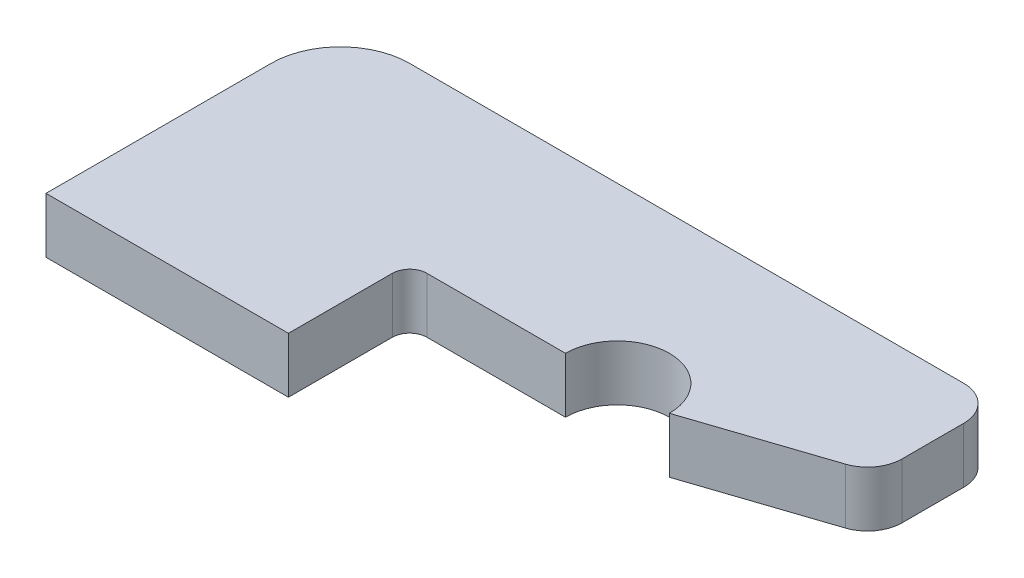
SolidWorks part; units mm, degrees
ref_plane "Plano frontal" through (0, 0, 0) normal (0, 0, 1) x (1, 0, 0)
ref_plane "Plano superior" through (0, 0, 0) normal (0, 1, 0) x (1, 0, 0)
ref_plane "Plano direito" through (0, 0, 0) normal (1, 0, 0) x (0, 0, -1)
sketch "Esboço2" plane through (0, 0, 0) normal (0, 1, 0) x (1, 0, 0)
  line L1 (-3.5, -4.25) -> (3.5, -4.25)
  line L2 (-3.5, -4.25) -> (-3.5, 2.25)
  line L3 (-1.5, 4.25) -> (3.5, 4.25)
  line L4 (3.5, -4.25) -> (3.5, 4.25)
  line L5 (-3.5, -4.25) -> (3.5, 4.25) construction
  line L6 (-3.5, 4.25) -> (3.5, -4.25) construction
  line L7 (3.5, 4.25) -> (15.5, 4.25)
  line L8 (3.5, 4.25) -> (3.5, -0.75)
  line L9 (3.5, -0.75) -> (15.5, -0.75)
  line L10 (15.5, 4.25) -> (15.5, -0.75)
  arc A0 (-1.5, 4.25) -> (-3.5, 2.25) centre (-1.5, 2.25) ccw
  point P0 (0, 0)
  dimension "D5" = 2
  dimension "D1" = 7
  dimension "D2" = 8.5
  dimension "D3" = 12
  dimension "D4" = 5
extrude "Ressalto-extrusão1" add sketch "Esboço2" along normal blind 1.6 contours L1 L4 L3 L2 | L10 L7 L4 L9
sketch "Esboço3" plane through (0, 1.6, 0) normal (0, 1, 0) x (1, 0, 0)
  line L0 (3.5, -0.75) -> (15.5, -0.75) construction
  circle A0 centre (9.5, -0.75) radius 1.5
  dimension "D1" = 3
extrude "Corte-extrusão1" cut sketch "Esboço3" against normal blind 1.6
sketch "Esboço4" plane through (0, 1.6, 0) normal (0, 1, 0) x (1, 0, 0)
  line L0 (11, -0.75) -> (15.5, 0.75)
  line L1 (15.5, 4.25) -> (15.5, -0.75) construction
  line L2 (15.5, 0.75) -> (15.5, -0.75)
  line L3 (15.5, -0.75) -> (11, -0.75)
extrude "Corte-extrusão2" cut sketch "Esboço4" against normal blind 1.6
fillet "Filete1" radius 1 1 edges at (15.5, 0.8, -0.75)
fillet "Filete2" radius 1 1 edges at (15.5, 0.8, -4.25)
fillet "Filete6" radius 0.5 1 edges at (3.5, 0.8, 0.75)
